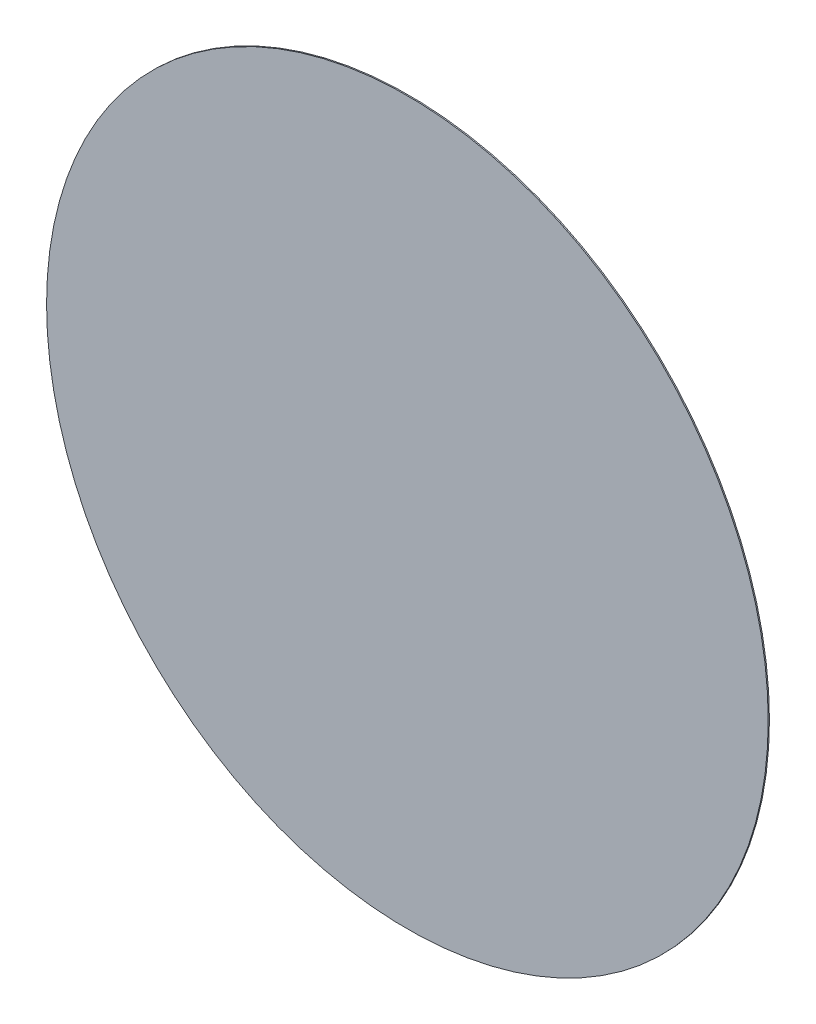
SolidWorks part; units mm, degrees
material "Homopolymère PP"
ref_plane "Plan de face" through (0, 0, 0) normal (0, 0, 1) x (1, 0, 0)
ref_plane "Plan de dessus" through (0, 0, 0) normal (0, 1, 0) x (1, 0, 0)
ref_plane "Plan de droite" through (0, 0, 0) normal (1, 0, 0) x (0, 0, -1)
sketch "Esquisse1" plane through (0, 0, 0) normal (0, 0, 1) x (1, 0, 0)
  circle A0 centre (0, 0) radius 15
  dimension "D1" = 30
extrude "Boss.-Extru.1" add sketch "Esquisse1" along normal blind 0.05
